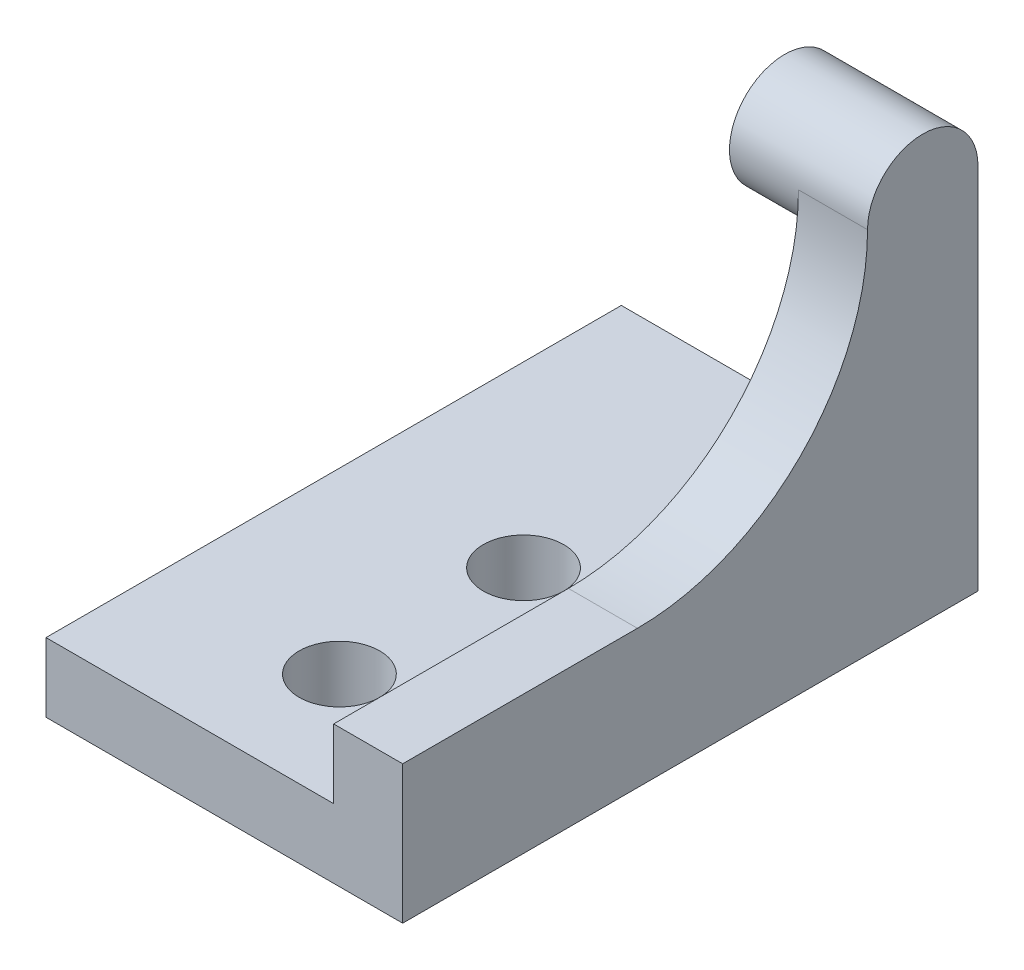
SolidWorks part; units mm, degrees
ref_plane "Plan de face" through (0, 0, 0) normal (0, 0, 1) x (1, 0, 0)
ref_plane "Plan de dessus" through (0, 0, 0) normal (0, 1, 0) x (1, 0, 0)
ref_plane "Plan de droite" through (0, 0, 0) normal (1, 0, 0) x (0, 0, -1)
sketch "Esquisse1" plane through (0, 0, 0) normal (1, 0, 0) x (0, 0, -1)
  circle A0 centre (0, 0) radius 2.4
  dimension "D1" = 4.8
extrude "Boss.-Extru.1" add sketch "Esquisse1" along normal blind 3
sketch "Esquisse2" plane through (3, 0, 0) normal (1, 0, 0) x (0, 0, -1)
  line L0 (-2.4, -13) -> (-22.6, -13)
  line L1 (-2.4, 0) -> (2.4, 0) construction
  line L2 (-2.4, 0) -> (-2.4, -13) construction
  line L3 (-2.4, -13) -> (2.4, -13)
  line L4 (2.4, 0) -> (2.4, -13)
  line L5 (-22.6, -13) -> (-22.6, -10)
  line L6 (-22.6, -10) -> (-12.4, -10)
  circle A0 centre (0, 0) radius 2.4 construction
  arc A1 (-2.4, 0) -> (2.4, 0) centre (0, 0) cw
  arc A2 (-2.4, 0) -> (-12.4, -10) centre (-12.4, 0) cw
  dimension "D4" = 10
  dimension "D1" = 13
  dimension "D2" = 25
  dimension "D3" = 3
extrude "Boss.-Extru.2" add sketch "Esquisse2" along normal blind 3
sketch "Esquisse3" plane through (0, -13, 0) normal (0, -1, 0) x (1, 0, 0)
  line L0 (3, 22.6) -> (3, -2.4) construction
  line L1 (6, -2.4) -> (-9.5, -2.4)
  line L2 (6, -2.4) -> (6, 22.6)
  line L3 (6, 22.6) -> (-9.5, 22.6)
  line L4 (-9.5, -2.4) -> (-9.5, 22.6)
  line L5 (-1.75, 17.6) -> (-1.75, 9.6) construction
  circle A0 centre (-1.75, 9.6) radius 1.75
  circle A1 centre (-1.75, 17.6) radius 1.75
  dimension "D2" = 3.5
  dimension "D1" = 4.75
  dimension "D3" = 12
  dimension "D4" = 15.5
  dimension "D5" = 25
  dimension "D6" = 8
extrude "Boss.-Extru.3" add sketch "Esquisse3" along normal blind 3
